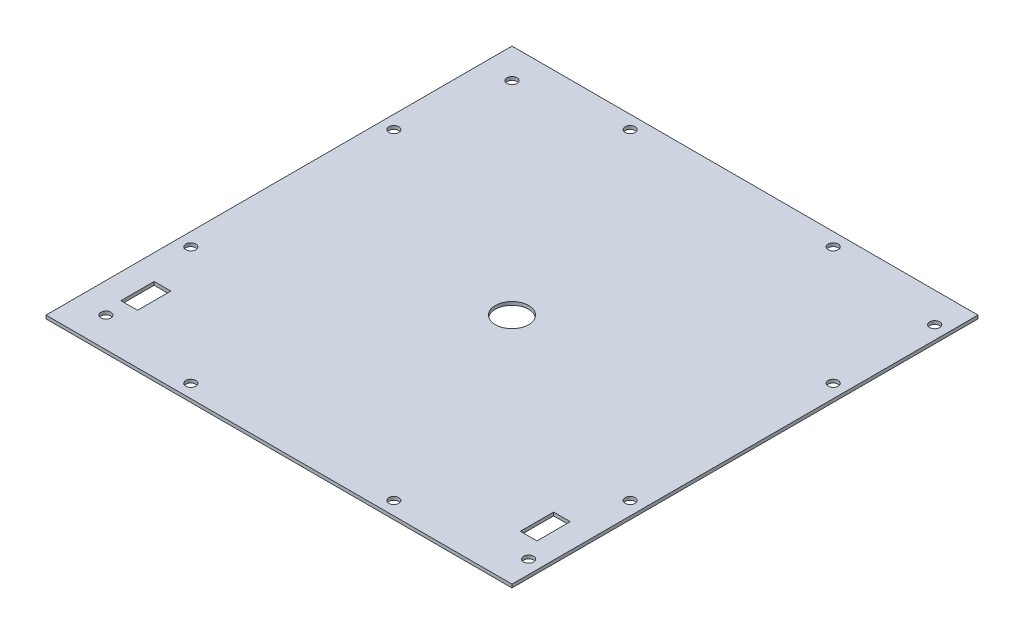
SolidWorks part; units mm, degrees
ref_plane "Alzado" through (0, 0, 0) normal (0, 0, 1) x (1, 0, 0)
ref_plane "Planta" through (0, 0, 0) normal (0, 1, 0) x (1, 0, 0)
ref_plane "Vista lateral" through (0, 0, 0) normal (1, 0, 0) x (0, 0, -1)
sketch "Croquis1" plane through (0, 0, 0) normal (0, 1, 0) x (1, 0, 0)
  line L0 (0, 0) -> (-62.5, 0) construction
  line L1 (-62.5, 0) -> (-62.5, 55) construction
  line L2 (-62.5, 55) -> (-55, 62.5) construction
  line L3 (-55, 62.5) -> (0, 62.5) construction
  line L4 (0, 62.5) -> (0, 0) construction
  line L5 (62.5, 55) -> (62.5, 0) construction
  line L6 (55, 62.5) -> (62.5, 55) construction
  line L7 (0, 62.5) -> (55, 62.5) construction
  line L8 (55, -62.5) -> (0, -62.5) construction
  line L9 (62.5, -55) -> (55, -62.5) construction
  line L10 (62.5, 0) -> (62.5, -55) construction
  line L11 (-62.5, -55) -> (-62.5, 0) construction
  line L12 (-55, -62.5) -> (-62.5, -55) construction
  line L13 (0, -62.5) -> (-55, -62.5) construction
  line L14 (0, -70) -> (0, -62.5) construction
  line L15 (0, 0) -> (-61, 0) construction
  line L16 (0, 0) -> (0, 61) construction
  line L17 (0, 61) -> (-61, 61) construction
  line L18 (-61, 0) -> (-61, 61) construction
  line L19 (0, 0) -> (-61, 0) construction
  line L20 (0, 0) -> (0, -61) construction
  line L21 (0, -61) -> (-61, -61) construction
  line L22 (-61, 0) -> (-61, -61) construction
  line L23 (0, 0) -> (66, 0) construction
  line L24 (0, 0) -> (0, -61) construction
  line L25 (0, -61) -> (66, -61) construction
  line L26 (66, 0) -> (66, -61) construction
  line L27 (0, 0) -> (66, 0) construction
  line L28 (0, 0) -> (0, 61) construction
  line L29 (0, 61) -> (66, 61) construction
  line L30 (66, 0) -> (66, 61) construction
  line L35 (25, -25) -> (-25, 25) construction
  line L36 (25, 25) -> (-25, -25) construction
  line L37 (70, -70) -> (-70, -70)
  line L38 (70, -70) -> (70, 70)
  line L39 (70, 70) -> (-70, 70)
  line L40 (-70, -70) -> (-70, 70)
  line L41 (70, -70) -> (-70, 70) construction
  line L42 (70, 70) -> (-70, -70) construction
  line L43 (-30.5, -66) -> (30.5, -66) construction
  line L57 (-55, 55) -> (55, -55) construction
  line L58 (-55, -55) -> (55, 55) construction
  circle A0 centre (-61, 61) radius 1.5
  circle A1 centre (66, 61) radius 1.5
  circle A2 centre (66, -61) radius 1.5
  circle A3 centre (-61, -61) radius 1.5
  circle A4 centre (66, 30.5) radius 1.5
  circle A5 centre (66, -30.5) radius 1.5
  circle A6 centre (-30.5, -66) radius 1.5
  circle A7 centre (30.5, -66) radius 1.5
  circle A8 centre (-30.5, 66) radius 1.5
  circle A9 centre (30.5, 66) radius 1.5
  circle A10 centre (-66, 30.5) radius 1.5
  circle A11 centre (-66, -30.5) radius 1.5
  circle A12 centre (0, 0) radius 5
  point P48 (0, -66)
  dimension "D6" = 3
  dimension "D9" = 4
  dimension "D10" = 3
  dimension "D12" = 10
  dimension "D1" = 55
  dimension "D2" = 62.5
  dimension "D4" = 61
  dimension "D5" = 66
  dimension "D7" = 110
  dimension "D8" = 140
  dimension "D11" = 61
  dimension "D3" = 4
extrude "Saliente-Extruir1" add sketch "Croquis1" along normal blind 1
sketch "Croquis2" plane through (0, 1, 0) normal (0, 1, 0) x (1, 0, 0)
  line L0 (57.5, -50) -> (55.5, -50) construction
  line L1 (57.5, -55) -> (62.5, -55)
  line L2 (57.5, -55) -> (57.5, -45)
  line L3 (57.5, -45) -> (62.5, -45)
  line L4 (62.5, -55) -> (62.5, -45)
  line L6 (70, -70) -> (70, 70) construction
  line L7 (0, 0) -> (0, 55) construction
  line L8 (55, 55) -> (-55, 55) construction
  line L9 (-57.5, -45) -> (-62.5, -45)
  line L10 (-62.5, -55) -> (-62.5, -45)
  line L11 (-57.5, -55) -> (-62.5, -55)
  line L12 (-57.5, -55) -> (-57.5, -45)
  line L14 (-70, -70) -> (70, -70) construction
  dimension "D1" = 2
  dimension "D2" = 7.5
  dimension "D3" = 10
  dimension "D4" = 5
  dimension "D5" = 15
extrude "Cortar-Extruir1" cut sketch "Croquis2" against normal blind 5
